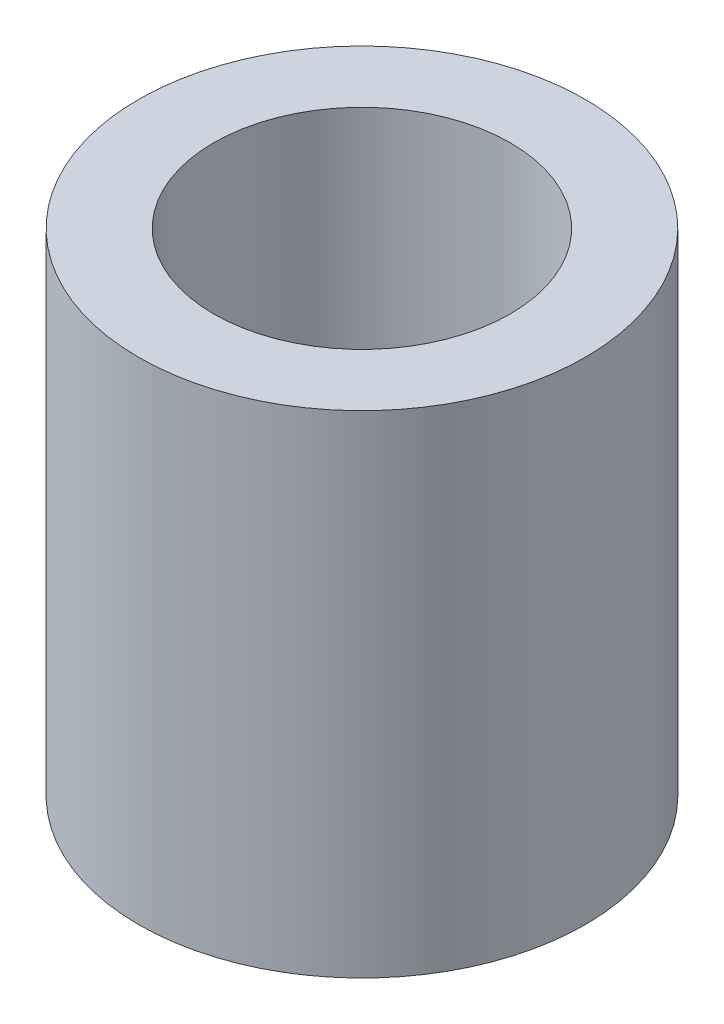
SolidWorks part; units mm, degrees
ref_plane "Front Plane" through (0, 0, 0) normal (0, 0, 1) x (1, 0, 0)
ref_plane "Top Plane" through (0, 0, 0) normal (0, 1, 0) x (1, 0, 0)
ref_plane "Right Plane" through (0, 0, 0) normal (1, 0, 0) x (0, 0, -1)
sketch "Sketch1" plane through (0, 0, 0) normal (0, 1, 0) x (1, 0, 0)
  circle A0 centre (0, 0) radius 6.35
  dimension "D1" = 12.7
extrude "Boss-Extrude1" add sketch "Sketch1" along normal blind 13.97
sketch "Sketch4" plane through (0, 13.97, 0) normal (0, 1, 0) x (1, 0, 0)
  point P0 (0, 0)
hole_wizard "Tap Drill for 3/8-24 Tap1" positions "Sketch4" profile "Sketch3" hole size "3/8-24" standard "ANSI Inch" end condition up to next
sketch "Sketch3" plane through (0, 13.97, 0) normal (1, 0, 0) x (0, 0, 1)
  line L0 (0, 0) -> (0, 13.97)
  line L1 (0, 13.97) -> (4.2164, 13.97)
  line L2 (4.2164, 13.97) -> (4.2164, 0)
  line L5 (4.2164, 0) -> (0, 0)
  line L11 (0, -6.35) -> (0, 107.95) construction
  dimension "Thru Hole Dia." = 8.4328
  dimension "Thru Hole Depth" = 13.97
sketch "Sketch11" plane through (0, 13.97, 0) normal (0, 1, 0) x (1, 0, 0)
  circle A0 centre (0, 0) radius 4
  dimension "D1" = 8
